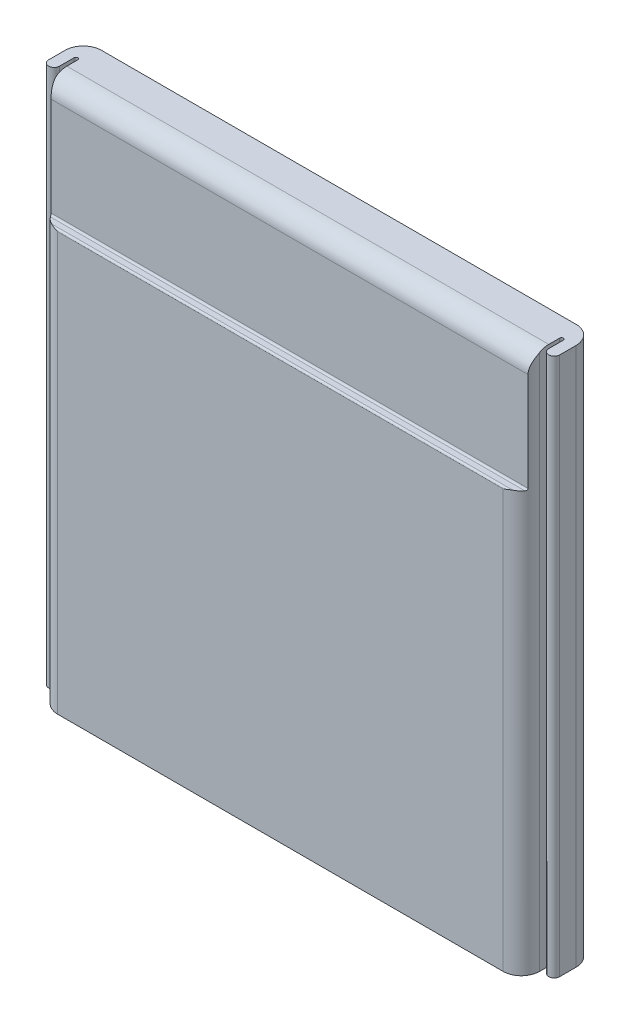
SolidWorks part; units mm, degrees
ref_plane "Front" through (0, 0, 0) normal (0, 0, 1) x (1, 0, 0)
ref_plane "Top" through (0, 0, 0) normal (0, 1, 0) x (1, 0, 0)
ref_plane "Right" through (0, 0, 0) normal (1, 0, 0) x (0, 0, -1)
sketch "Эскиз1" plane through (0, 0, 0) normal (0, 1, 0) x (1, 0, 0)
  line L0 (-13, 0) -> (13, 0)
  line L1 (-12.2, -3.2) -> (12.2, -3.2)
  line L2 (-14, -1) -> (-14, -1.9)
  line L3 (14, -1) -> (14, -1.9)
  line L4 (-13.2, -2.2) -> (-13.2, -1.1)
  line L5 (13.2, -1.1) -> (13.2, -2.2)
  line L6 (13.4, -1.9) -> (13.4, -1.1)
  line L7 (-13.4, -1.9) -> (-13.4, -1.1)
  arc A0 (-13, 0) -> (-14, -1) centre (-13, -1) ccw
  arc A1 (13, 0) -> (14, -1) centre (13, -1) cw
  arc A2 (-13.2, -2.2) -> (-12.2, -3.2) centre (-12.2, -2.2) ccw
  arc A3 (13.2, -2.2) -> (12.2, -3.2) centre (12.2, -2.2) cw
  arc A4 (14, -1.9) -> (13.4, -1.9) centre (13.7, -1.9) cw
  arc A5 (13.2, -1.1) -> (13.4, -1.1) centre (13.3, -1.1) cw
  arc A6 (-14, -1.9) -> (-13.4, -1.9) centre (-13.7, -1.9) ccw
  arc A7 (-13.2, -1.1) -> (-13.4, -1.1) centre (-13.3, -1.1) ccw
  point P20 (13.3, -1)
  point P21 (13.7, -2.2)
  point P27 (-13.3, -1)
  point P28 (-13.7, -2.2)
  dimension "D1" = 28
  dimension "D3" = 1
  dimension "D4" = 1
  dimension "D5" = 0.3
  dimension "D6" = 0.1
  dimension "D2" = 3.2
extrude "Бобышка-Вытянуть1" add sketch "Эскиз1" along normal mid plane 29.5
sketch "Эскиз2" plane through (0, 0, 0) normal (1, 0, 0) x (0, 0, -1)
  line L0 (-2.7, 13.75) -> (-2.7, 8.35)
  line L1 (-2.8, 8.25) -> (-3.1, 8.25)
  line L2 (-3.2, 14.75) -> (-3.2, 8.15)
  line L3 (-3.2, 14.75) -> (-3.2, -14.75) construction
  line L6 (-3.2, 14.75) -> (-1.7, 14.75)
  line L7 (0, 14.75) -> (-1, 14.75) construction
  arc A0 (-2.7, 8.35) -> (-2.8, 8.25) centre (-2.8, 8.35) cw
  arc A1 (-3.1, 8.25) -> (-3.2, 8.15) centre (-3.1, 8.15) ccw
  arc A2 (-1.7, 14.75) -> (-2.7, 13.75) centre (-1.7, 13.75) ccw
  dimension "D1" = 0.1
  dimension "D4" = 1
  dimension "D2" = 2.7
  dimension "D3" = 6.5
extrude "Вырез-Вытянуть1" cut sketch "Эскиз2" against normal up to next and the other way up to next
